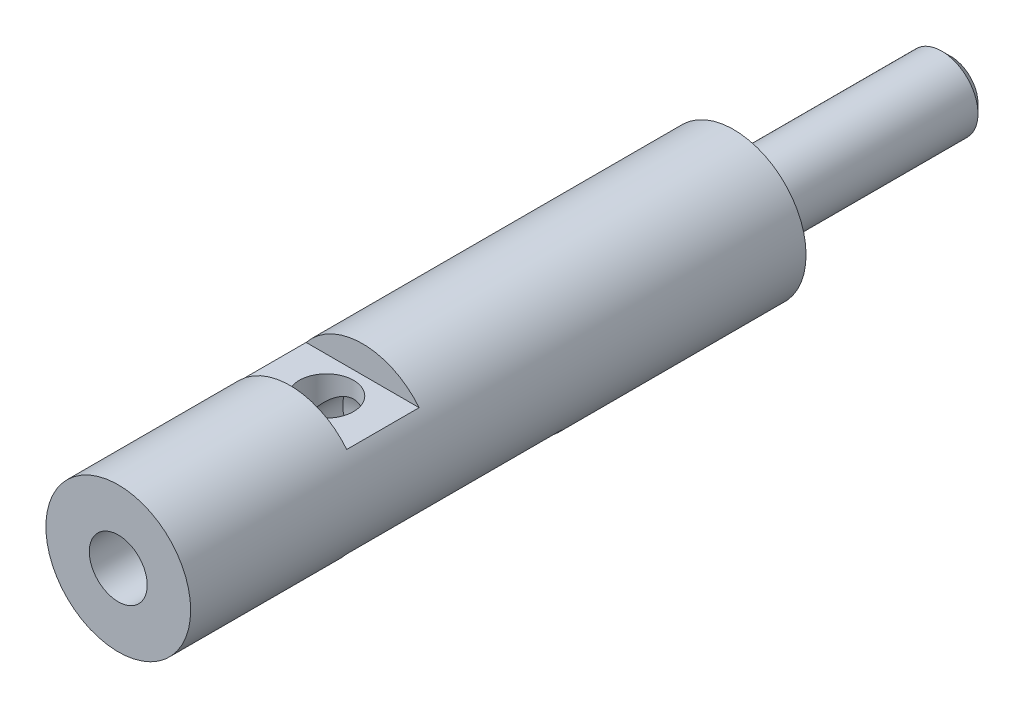
SolidWorks part; units mm, degrees
ref_plane "Front Plane" through (0, 0, 0) normal (0, 0, 1) x (1, 0, 0)
ref_plane "Top Plane" through (0, 0, 0) normal (0, 1, 0) x (1, 0, 0)
ref_plane "Right Plane" through (0, 0, 0) normal (1, 0, 0) x (0, 0, -1)
sketch "Sketch1" plane through (0, 0, 0) normal (0, 0, 1) x (1, 0, 0)
  circle A0 centre (0, 0) radius 4
  dimension "D1" = 8
extrude "Boss-Extrude1" add sketch "Sketch1" along normal blind 34
sketch "Sketch2" plane through (0, 0, 0) normal (0, 0, -1) x (-1, 0, 0)
  circle A0 centre (0, 0) radius 2
  dimension "D1" = 4
extrude "Boss-Extrude2" add sketch "Sketch2" along normal blind 12
chamfer "Chamfer1" distance 0.5 angle 45 1 edges at (-2, 0, -12)
hole_wizard "Ø3.2 (3.2) Diameter Hole1" positions "Sketch3" profile "Sketch4" hole size "Ø3.2" standard "ANSI Metric"
sketch "Sketch3" plane through (0, 0, 34) normal (0, 0, 1) x (1, 0, 0)
  point P0 (0, 0)
sketch "Sketch4" plane through (0, 0, 34) normal (1, 0, 0) x (0, -1, 0)
  line L0 (0, 0) -> (0, 14.9614)
  line L1 (0, 14.9614) -> (1.6, 14)
  line L2 (1.6, 14) -> (1.6, 0)
  line L5 (1.6, 0) -> (0, 0)
  line L10 (0, 14.9614) -> (-1.6, 14) construction
  line L11 (0, -6.35) -> (0, 107.95) construction
  dimension "Hole Dia." = 3.2
  dimension "Hole Depth" = 14
  dimension "Drill Angle" = 118
sketch "Sketch5" plane through (0, 0, 0) normal (1, 0, 0) x (0, 0, -1)
  line L11 (-34, -4) -> (0, -4) construction
  line L12 (-24.5, -4) -> (-12.5, -4)
  line L13 (-24.5, -4) -> (-24.5, -2.5)
  line L14 (-24.5, -2.5) -> (-12.5, -2.5)
  line L15 (-12.5, -4) -> (-12.5, -2.5)
  line L16 (0, 4) -> (-34, 4) construction
  line L17 (-24.5, 4) -> (-20.5, 4)
  line L18 (-24.5, 4) -> (-24.5, 2.5)
  line L19 (-24.5, 2.5) -> (-20.5, 2.5)
  line L20 (-20.5, 4) -> (-20.5, 2.5)
  line L21 (-34, 4) -> (-34, -4) construction
  dimension "D1" = 1.5
  dimension "D2" = 1.5
  dimension "D3" = 12
  dimension "D4" = 4
  dimension "D5" = 9.5
extrude "Cut-Extrude2" cut sketch "Sketch5" against normal through all and the other way through all
hole_wizard "Ø3.0 (3) Diameter Hole1" positions "Sketch6" profile "Sketch7" hole size "Ø3.0" standard "ANSI Metric"
sketch "Sketch6" plane through (0, 2.5, 0) normal (0, 1, 0) x (1, 0, 0)
  line L0 (-3.1225, -24.5) -> (3.1225, -20.5) construction
  point P7 (0, -22.5)
sketch "Sketch7" plane through (0, 2.5, 22.5) normal (1, 0, 0) x (0, 0, 1)
  line L0 (0, 0) -> (0, 0.9)
  line L1 (0, 0.9) -> (1.5, 0.9)
  line L2 (1.5, 0.9) -> (1.5, 0)
  line L5 (1.5, 0) -> (0, 0)
  line L11 (0, -6.35) -> (0, 107.95) construction
  dimension "Thru Hole Dia." = 3
  dimension "Thru Hole Depth" = 0.9
